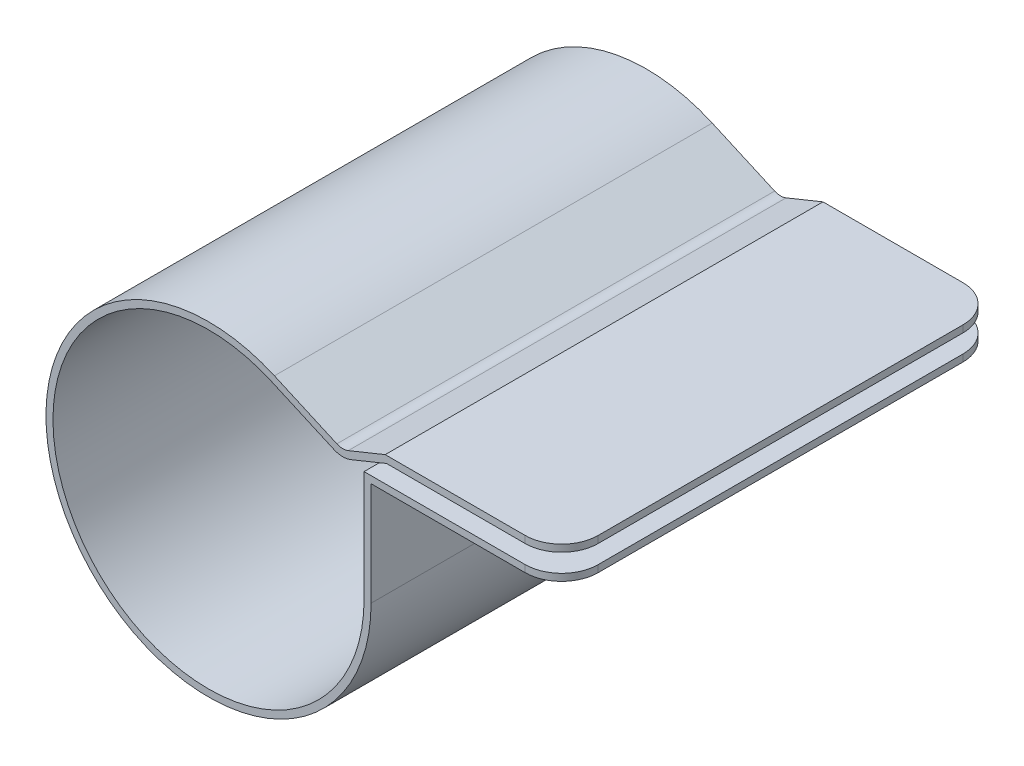
SolidWorks part; units mm, degrees
material "1060 Alloy"
ref_plane "Front Plane" through (0, 0, 0) normal (0, 0, 1) x (1, 0, 0)
ref_plane "Top Plane" through (0, 0, 0) normal (0, 1, 0) x (1, 0, 0)
ref_plane "Right Plane" through (0, 0, 0) normal (1, 0, 0) x (0, 0, -1)
sketch "Sketch1" plane through (0, 0, 0) normal (0, 0, 1) x (1, 0, 0)
  line L0 (0, 30.988) -> (0, -30.988) construction
  line L1 (-30.988, -30.988) -> (30.988, -30.988)
  line L2 (-30.988, -30.988) -> (-30.988, 30.988)
  line L3 (-30.988, 30.988) -> (30.988, 30.988)
  line L4 (30.988, -30.988) -> (30.988, 30.988)
  line L5 (-30.988, -30.988) -> (30.988, 30.988) construction
  line L6 (-30.988, 30.988) -> (30.988, -30.988) construction
  line L7 (-30.988, 0) -> (30.988, 0) construction
  circle A0 centre (0, 0) radius 27.0764
  circle A1 centre (-23.368, 23.368) radius 2.54
  circle A2 centre (-23.368, -23.368) radius 2.54
  circle A3 centre (23.368, -23.368) radius 2.54
  circle A4 centre (23.368, 23.368) radius 2.54
  point P20 (0, 0)
  dimension "D1" = 54.1528
  dimension "D2" = 5.08
  dimension "D3" = 7.62
  dimension "D4" = 61.976
sketch "Sketch2" plane through (0, 0, 0) normal (0, 0, 1) x (1, 0, 0)
  line L0 (30.988, 30.988) -> (30.988, 22.4053)
  line L1 (30.988, -30.988) -> (30.988, 30.988) construction
  line L2 (30.988, 22.4053) -> (30.988, 19.2303)
  line L4 (25.908, 23.368) -> (25.908, 27.0764) construction
  line L7 (27.0764, 0) -> (27.0764, 19.2303)
  line L8 (27.0764, 19.2303) -> (61.468, 19.2303)
  line L9 (28.2956, 18.0111) -> (61.468, 18.0111)
  line L10 (28.2956, 0) -> (28.2956, 18.0111)
  line L15 (61.468, 19.2303) -> (61.468, 18.0111)
  line L16 (10.978, 24.751) -> (21.8438, 19.9316)
  line L17 (26.3833, 28.2956) -> (31.8132, 23.3028) construction
  line L18 (25.908, 27.0764) -> (30.988, 22.4053) construction
  line L19 (0, 27.0764) -> (25.908, 27.0764) construction
  line L20 (0, 28.2956) -> (26.3833, 28.2956) construction
  line L21 (24.7825, 19.8851) -> (30.988, 22.4053)
  line L22 (30.988, 22.4053) -> (61.468, 22.4053)
  line L23 (24.3238, 21.0147) -> (30.7499, 23.6245)
  line L24 (30.7499, 23.6245) -> (61.468, 23.6245)
  line L25 (11.4723, 25.8655) -> (22.3382, 21.0461)
  line L26 (61.468, 22.4053) -> (61.468, 23.6245)
  line L27 (80.815, 39.7717) -> (81.04, 39.6592)
  arc A0 (10.978, 24.751) -> (27.0764, 0) centre (0, 0) ccw
  circle A1 centre (23.368, 23.368) radius 2.54 construction
  circle A2 centre (0, 0) radius 27.0764 construction
  arc A3 (0, 28.2956) -> (28.2956, 0) centre (0, 0) ccw
  circle A4 centre (23.368, 23.368) radius 3.7592
  arc A5 (0, 27.0764) -> (27.0764, 0) centre (0, 0) ccw construction
  arc A6 (11.4723, 25.8655) -> (28.2956, 0) centre (0, 0) ccw
  circle A7 centre (23.368, 23.368) radius 2.54
  dimension "D5" = 1.2192
  dimension "D1" = 8.5827
  dimension "D2" = 3.175
  dimension "D3" = 30.48
  dimension "D4" = 1.2192
  dimension "D6" = 1.2192
extrude "Boss-Extrude1" add sketch "Sketch2" along normal blind 76.2
fillet "Fillet2" radius 6.35 4 edges at (61.468, 23.0149, 0) (61.468, 23.0149, 76.2) (61.468, 18.6207, 0) (61.468, 18.6207, 76.2)
sketch "Bend-Lines3" [suppressed] plane through (0, 0, 0) normal (0, 1, 0) x (1, 0, 0)
sketch "Bounding-Box3" [suppressed] plane through (0, 0, 0) normal (0, 1, 0) x (1, 0, 0)
